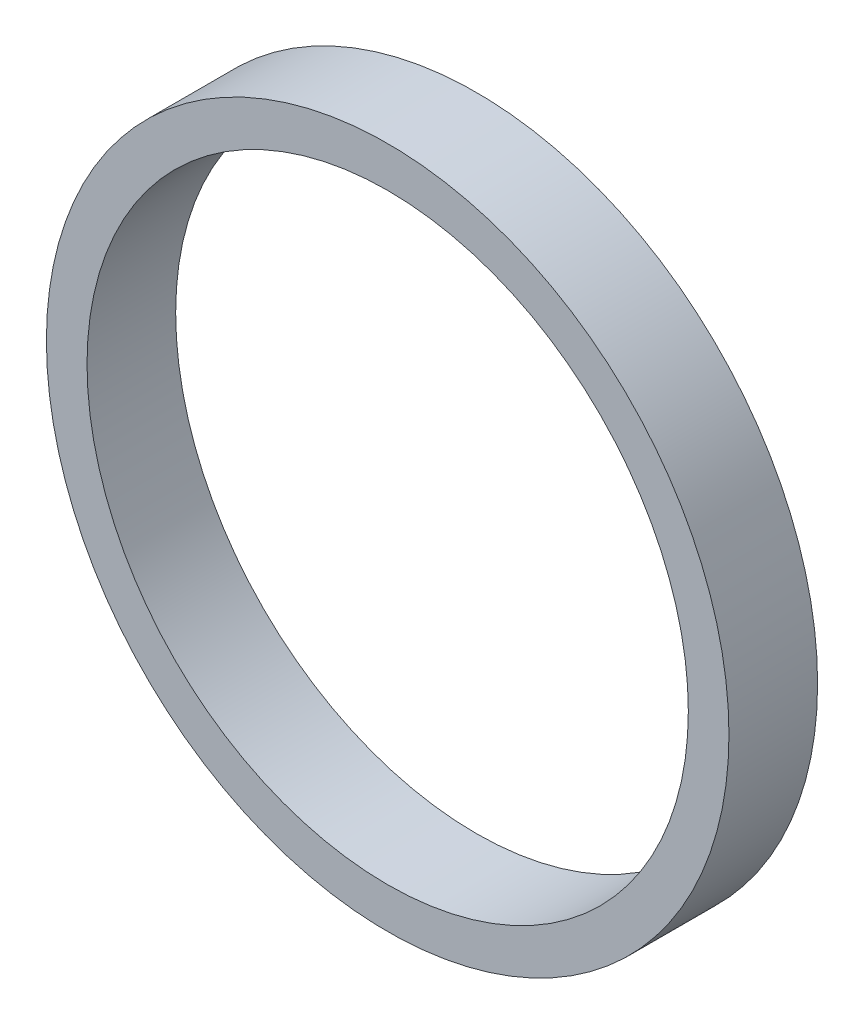
SolidWorks part; units mm, degrees
material "ABS"
ref_plane "Front Plane" through (0, 0, 0) normal (0, 0, 1) x (1, 0, 0)
ref_plane "Top Plane" through (0, 0, 0) normal (0, 1, 0) x (1, 0, 0)
ref_plane "Right Plane" through (0, 0, 0) normal (1, 0, 0) x (0, 0, -1)
sketch "Sketch1" plane through (0, 0, 0) normal (0, 0, 1) x (1, 0, 0)
  circle A0 centre (0, 0) radius 5.0875
  circle A1 centre (0, 0) radius 5.775
  dimension "D1" = 10.175
  dimension "D2" = 11.55
extrude "Boss-Extrude1" add sketch "Sketch1" along normal blind 1.5
equation "\"RingPinShaft\"= 5.05"
equation "\"CenterBearingOut\"=32.05"
equation "\"RingPostIn\"=5.15"
equation "\"CamBearingOut\"=15.1"
equation "\"DiskOutputShaft\"=10.1"
equation "\"CenterShaft\"=25.2"
equation "\"Eccentricity\"=2"
equation "\"CycCamShaft\"=10.05"
equation "\"D1@Sketch1\"=\"CycCamShaft\" + 0.125"
equation "\"D2@Sketch1\"=\"CycCamShaft\"+1.5"
